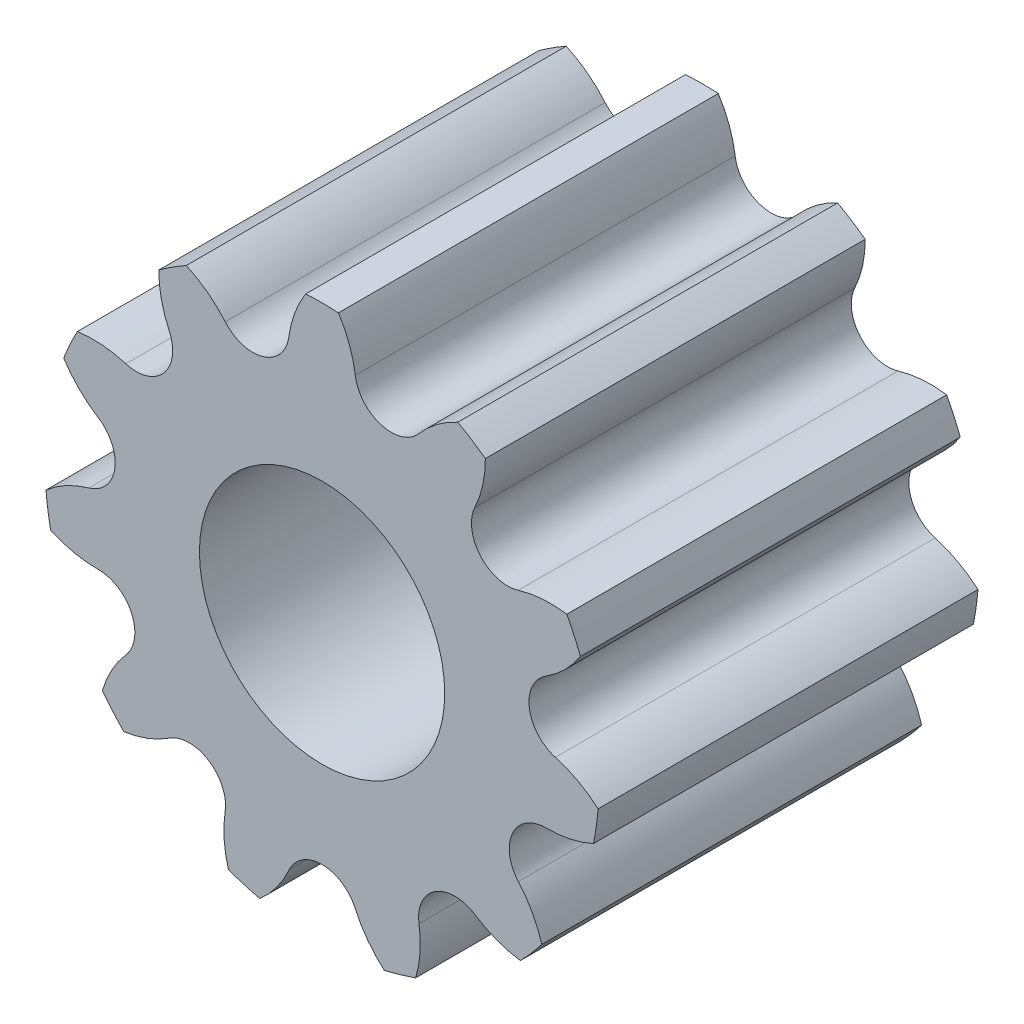
SolidWorks part; units mm, degrees
ref_plane "Front Plane" through (0, 0, 0) normal (0, 0, 1) x (1, 0, 0)
ref_plane "Top Plane" through (0, 0, 0) normal (0, 1, 0) x (1, 0, 0)
ref_plane "Right Plane" through (0, 0, 0) normal (1, 0, 0) x (0, 0, -1)
sketch "Sketch1" plane through (0, 0, 0) normal (0, 0, 1) x (1, 0, 0)
  circle A0 centre (0, 0) radius 1.55
  circle A1 centre (0, 0) radius 3.5 construction
  arc A2 (-1.225, -2.6808) -> (-1.2205, -2.6359) centre (-1.6786, -2.6119) ccw
  arc A3 (-0.3984, -2.8773) -> (-0.4188, -2.9175) centre (0, -3.1048) ccw
  arc A4 (0.3984, -2.8773) -> (-0.3984, -2.8773) centre (0, -3.1048) ccw
  arc A5 (0.4188, -2.9175) -> (0.3984, -2.8773) centre (0, -3.1048) ccw
  arc A6 (1.2205, -2.6359) -> (1.225, -2.6808) centre (1.6786, -2.6119) ccw
  arc A7 (1.9296, -2.228) -> (1.8907, -2.2052) centre (1.6786, -2.6119) ccw
  arc A8 (2.8279, -0.8311) -> (2.7828, -0.8329) centre (2.8242, -1.2898) ccw
  arc A9 (2.4518, -1.5576) -> (2.4799, -1.5929) centre (2.8242, -1.2898) ccw
  arc A10 (2.9047, 0.0152) -> (2.9474, 0.0007) centre (3.0732, 0.4419) ccw
  arc A11 (2.8283, 0.8297) -> (2.7913, 0.8038) centre (3.0732, 0.4419) ccw
  arc A12 (2.8279, -0.8311) -> (3.4296, -0.7022) centre (2.8391, 0.586) ccw
  arc A13 (2.7828, -0.8329) -> (2.4518, -1.5576) centre (2.8242, -1.2898) ccw
  arc A14 (2.7766, -2.1321) -> (2.4799, -1.5929) centre (1.4164, -2.5294) ccw
  arc A15 (2.5055, -2.4449) -> (2.7766, -2.1321) centre (0, 0) ccw
  arc A16 (1.9296, -2.228) -> (2.5055, -2.4449) centre (2.7052, -1.042) ccw
  arc A17 (1.8907, -2.2052) -> (1.2205, -2.6359) centre (1.6786, -2.6119) ccw
  arc A18 (1.1831, -3.2948) -> (1.225, -2.6808) centre (-0.176, -2.8936) ccw
  arc A19 (0.786, -3.4114) -> (1.1831, -3.2948) centre (0, 0) ccw
  arc A20 (0.4188, -2.9175) -> (0.786, -3.4114) centre (1.7124, -2.3391) ccw
  arc A21 (-0.786, -3.4114) -> (-0.4188, -2.9175) centre (-1.7124, -2.3391) ccw
  arc A22 (-1.1831, -3.2948) -> (-0.786, -3.4114) centre (0, 0) ccw
  arc A23 (-1.225, -2.6808) -> (-1.1831, -3.2948) centre (0.176, -2.8936) ccw
  arc A24 (3.4296, -0.7022) -> (3.4885, -0.2925) centre (0, 0) ccw
  arc A25 (3.4885, -0.2925) -> (2.9474, 0.0007) centre (2.559, -1.3621) ccw
  arc A26 (2.7913, 0.8038) -> (2.9047, 0.0152) centre (3.0732, 0.4419) ccw
  arc A27 (2.8283, 0.8297) -> (3.2648, 1.2634) centre (2.0716, 2.0279) ccw
  arc A28 (3.2648, 1.2634) -> (3.0928, 1.64) centre (0, 0) ccw
  arc A29 (-1.8907, -2.2052) -> (-1.9296, -2.228) centre (-1.6786, -2.6119) ccw
  arc A30 (-2.4799, -1.5929) -> (-2.4518, -1.5576) centre (-2.8242, -1.2898) ccw
  arc A31 (-2.7828, -0.8329) -> (-2.8279, -0.8311) centre (-2.8242, -1.2898) ccw
  arc A32 (-2.9474, 0.0007) -> (-2.9047, 0.0152) centre (-3.0732, 0.4419) ccw
  arc A33 (-2.7913, 0.8038) -> (-2.8283, 0.8297) centre (-3.0732, 0.4419) ccw
  arc A34 (-1.2205, -2.6359) -> (-1.8907, -2.2052) centre (-1.6786, -2.6119) ccw
  arc A35 (-2.5055, -2.4449) -> (-1.9296, -2.228) centre (-2.7052, -1.042) ccw
  arc A36 (-2.7766, -2.1321) -> (-2.5055, -2.4449) centre (0, 0) ccw
  arc A37 (-2.4799, -1.5929) -> (-2.7766, -2.1321) centre (-1.4164, -2.5294) ccw
  arc A38 (-2.4518, -1.5576) -> (-2.7828, -0.8329) centre (-2.8242, -1.2898) ccw
  arc A39 (-3.4296, -0.7022) -> (-2.8279, -0.8311) centre (-2.8391, 0.586) ccw
  arc A40 (-3.4885, -0.2925) -> (-3.4296, -0.7022) centre (0, 0) ccw
  arc A41 (-2.9474, 0.0007) -> (-3.4885, -0.2925) centre (-2.559, -1.3621) ccw
  arc A42 (-2.9047, 0.0152) -> (-2.7913, 0.8038) centre (-3.0732, 0.4419) ccw
  arc A43 (-3.2648, 1.2634) -> (-2.8283, 0.8297) centre (-2.0716, 2.0279) ccw
  arc A44 (-2.4792, 1.5941) -> (-2.4354, 1.5832) centre (-2.3464, 2.0332) ccw
  arc A45 (-1.9137, 2.1853) -> (-1.9307, 2.2271) centre (-2.3464, 2.0332) ccw
  arc A46 (-1.2238, 2.6814) -> (-1.1929, 2.6485) centre (-0.8747, 2.979) ccw
  arc A47 (-0.4284, 2.873) -> (-0.4202, 2.9173) centre (-0.8747, 2.979) ccw
  arc A48 (2.4354, 1.5832) -> (2.4792, 1.5941) centre (2.3464, 2.0332) ccw
  arc A49 (1.9307, 2.2271) -> (1.9137, 2.1853) centre (2.3464, 2.0332) ccw
  arc A50 (3.0928, 1.64) -> (2.4792, 1.5941) centre (2.8892, 0.2376) ccw
  arc A51 (1.9137, 2.1853) -> (2.4354, 1.5832) centre (2.3464, 2.0332) ccw
  arc A52 (1.9307, 2.2271) -> (2.0635, 2.828) centre (0.6464, 2.826) ccw
  arc A53 (2.0635, 2.828) -> (1.7152, 3.0518) centre (0, 0) ccw
  arc A54 (1.1929, 2.6485) -> (1.2238, 2.6814) centre (0.8747, 2.979) ccw
  arc A55 (0.4202, 2.9173) -> (0.4284, 2.873) centre (0.8747, 2.979) ccw
  arc A56 (1.7152, 3.0518) -> (1.2238, 2.6814) centre (2.3021, 1.7619) ccw
  arc A57 (0.4284, 2.873) -> (1.1929, 2.6485) centre (0.8747, 2.979) ccw
  arc A58 (0.4202, 2.9173) -> (0.207, 3.4946) centre (-0.984, 2.7268) ccw
  arc A59 (0.207, 3.4946) -> (0, 3.5008) centre (0, 0) ccw
  arc A60 (0, 3.5008) -> (-0.207, 3.4946) centre (0, 0) ccw
  arc A61 (-0.207, 3.4946) -> (-0.4202, 2.9173) centre (0.984, 2.7268) ccw
  arc A62 (-1.1929, 2.6485) -> (-0.4284, 2.873) centre (-0.8747, 2.979) ccw
  arc A63 (-1.2238, 2.6814) -> (-1.7152, 3.0518) centre (-2.3021, 1.7619) ccw
  arc A64 (-1.7152, 3.0518) -> (-2.0635, 2.828) centre (0, 0) ccw
  arc A65 (-2.0635, 2.828) -> (-1.9307, 2.2271) centre (-0.6464, 2.826) ccw
  arc A66 (-2.4354, 1.5832) -> (-1.9137, 2.1853) centre (-2.3464, 2.0332) ccw
  arc A67 (-2.4792, 1.5941) -> (-3.0928, 1.64) centre (-2.8892, 0.2376) ccw
  arc A68 (-3.0928, 1.64) -> (-3.2648, 1.2634) centre (0, 0) ccw
  circle A69 centre (0, 0) radius 3.5008
  dimension "D1" = 3.1
  dimension "D2" = 7
extrude "Boss-Extrude1" add sketch "Sketch1" along normal blind 4.8 contours A67 A68 A43 A33 A42 A32 A41 A40 A39 A31 A38 A30 A37 A36 A35 A29 A34 A2 A23 A22 A21 A3 A4 A5 A20 A19 A18 A6 A17 A7 A16 A15 A14 A9 A13 A8 A12 A24 A25 A10 A26 A11 A27 A28 A50 A48 A51 A49 A52 A53 A56
